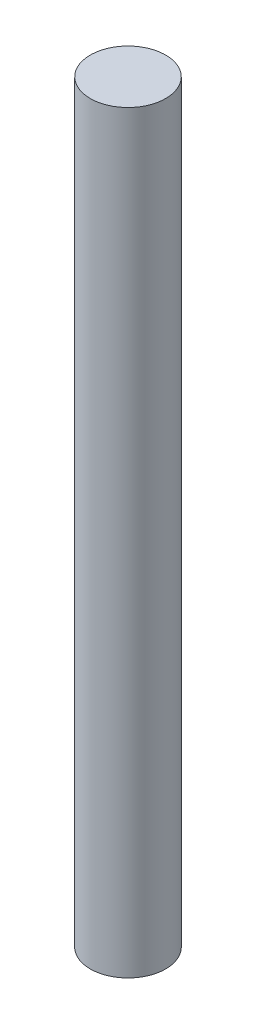
SolidWorks part; units mm, degrees
material "黄铜"
ref_plane "前视基准面" through (0, 0, 0) normal (0, 0, 1) x (1, 0, 0)
ref_plane "上视基准面" through (0, 0, 0) normal (0, 1, 0) x (1, 0, 0)
ref_plane "右视基准面" through (0, 0, 0) normal (1, 0, 0) x (0, 0, -1)
sketch "草图1" plane through (0, 0, 0) normal (0, 1, 0) x (1, 0, 0)
  circle A0 centre (-7.2501, 1.8433) radius 1.5
  dimension "D1" = 3
extrude "凸台-拉伸1" add sketch "草图1" along normal blind 30
